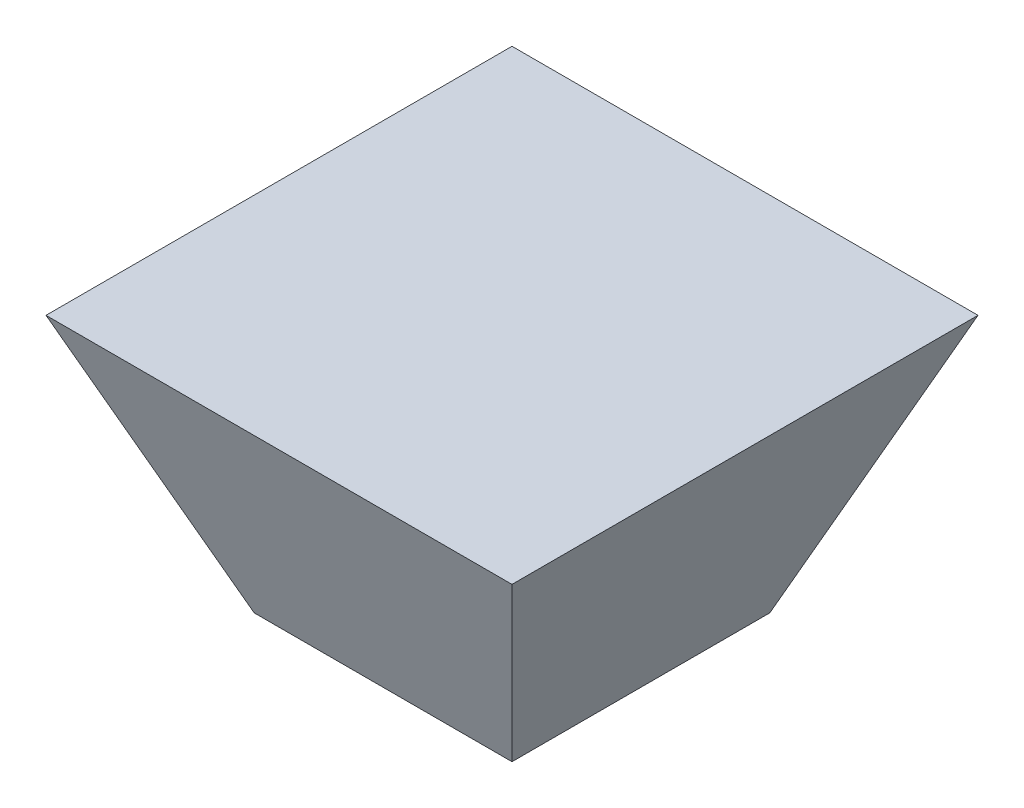
SolidWorks part; units mm, degrees
ref_plane "Front Plane" through (0, 0, 0) normal (0, 0, 1) x (1, 0, 0)
ref_plane "Top Plane" through (0, 0, 0) normal (0, 1, 0) x (1, 0, 0)
ref_plane "Right Plane" through (0, 0, 0) normal (1, 0, 0) x (0, 0, -1)
sketch "Sketch1" plane through (0, 0, 0) normal (0, 1, 0) x (1, 0, 0)
  line L1 (56.35, -56.35) -> (56.35, 56.35)
  line L2 (56.35, 56.35) -> (-56.35, 56.35)
  line L3 (-56.35, 56.35) -> (-56.35, -56.35)
  line L4 (-56.35, -56.35) -> (56.35, -56.35)
  circle A0 centre (0, 0) radius 56.35 construction
  dimension "D1" = 112.7
  dimension "D2" = 112.7
extrude "Boss-Extrude1" add sketch "Sketch1" along normal blind 112.7 draft 22 draft outward yes
